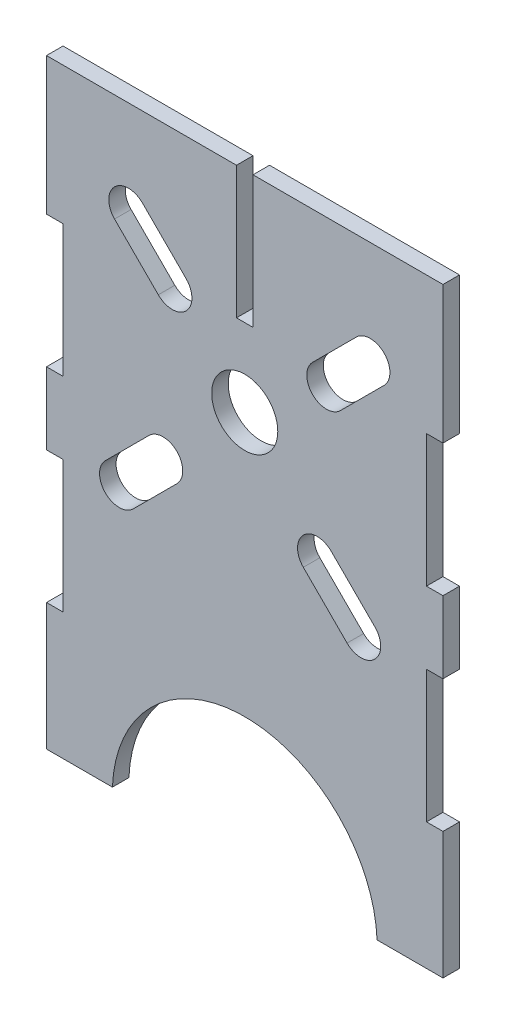
SolidWorks part; units mm, degrees
material "CARBON FIBERR"
ref_plane "Front Plane" through (0, 0, 0) normal (0, 0, 1) x (1, 0, 0)
ref_plane "Top Plane" through (0, 0, 0) normal (0, 1, 0) x (1, 0, 0)
ref_plane "Right Plane" through (0, 0, 0) normal (1, 0, 0) x (0, 0, -1)
sketch "Sketch9" plane through (0, 0, -50.8) normal (0, 0, 1) x (1, 0, 0)
  line L0 (24.1179, 20.5699) -> (15.7086, 12.1607) construction
  line L1 (1.5875, 14.9347) -> (-1.5875, 14.9347) construction
  line L2 (1.5875, 14.9347) -> (-1.5875, 14.9347)
  line L3 (-1.5875, 40.3347) -> (-1.5875, 14.9347) construction
  line L4 (-1.5875, 40.3347) -> (-1.5875, 14.9347)
  line L5 (1.5875, 40.3347) -> (1.5875, 14.9347) construction
  line L6 (1.5875, 40.3347) -> (1.5875, 14.9347)
  line L7 (-1.5875, 40.3347) -> (-38.1, 40.3347)
  line L8 (-38.1, 40.3347) -> (-38.1, -76.0967)
  line L9 (-38.1, -76.0967) -> (-25.4496, -76.0967)
  line L10 (25.4496, -76.0967) -> (38.1, -76.0967)
  line L11 (38.1, -76.0967) -> (38.1, 40.3347)
  line L12 (38.1, 40.3347) -> (1.5875, 40.3347)
  line L13 (1.5875, -76.0967) -> (-1.5875, -76.0967) construction
  line L14 (1.5875, -50.6967) -> (-1.5875, -50.6967) construction
  line L15 (1.5875, -50.6967) -> (-1.5875, -50.6967)
  line L16 (26.795, 17.8928) -> (18.3857, 9.4836)
  line L17 (21.4408, 23.247) -> (13.0315, 14.8378)
  line L18 (-22.3439, 22.3439) -> (-13.9347, 13.9347) construction
  line L19 (-22.3439, -22.3439) -> (22.3439, -22.3439) construction
  line L20 (-22.3439, -22.3439) -> (-22.3439, 22.3439) construction
  line L21 (-22.3439, 22.3439) -> (22.3439, 22.3439) construction
  line L22 (22.3439, -22.3439) -> (22.3439, 22.3439) construction
  line L23 (-22.3439, -22.3439) -> (22.3439, 22.3439) construction
  line L24 (-22.3439, 22.3439) -> (22.3439, -22.3439) construction
  line L25 (-19.6668, 25.021) -> (-11.2576, 16.6118)
  line L26 (-25.021, 19.6668) -> (-16.6118, 11.2576)
  line L27 (22.3439, -25.8918) -> (13.9347, -17.4826) construction
  line L28 (19.6668, -28.5689) -> (11.2576, -20.1597)
  line L29 (25.021, -23.2147) -> (16.6118, -14.8055)
  line L30 (-24.1179, -24.1179) -> (-15.7086, -15.7086) construction
  line L31 (-26.795, -21.4408) -> (-18.3857, -13.0315)
  line L32 (-21.4408, -26.795) -> (-13.0315, -18.3857)
  line L33 (-38.1, 39.3347) -> (-1.5875, 39.3347)
  line L34 (1.5875, 39.3347) -> (38.1, 39.3347)
  line L35 (38.1, 13.9347) -> (34.925, 13.9347)
  line L36 (34.925, 13.9347) -> (34.925, -11.4653)
  line L37 (34.925, -11.4653) -> (38.1, -11.4653)
  line L38 (38.1, -25.2967) -> (34.925, -25.2967)
  line L39 (34.925, -25.2967) -> (34.925, -50.6967)
  line L40 (34.925, -50.6967) -> (38.1, -50.6967)
  line L41 (-38.1, 13.9347) -> (-34.925, 13.9347)
  line L42 (-34.925, 13.9347) -> (-34.925, -11.4653)
  line L43 (-34.925, -11.4653) -> (-38.1, -11.4653)
  line L44 (-38.1, -25.2967) -> (-34.925, -25.2967)
  line L45 (-34.925, -25.2967) -> (-34.925, -50.6967)
  line L46 (-34.925, -50.6967) -> (-38.1, -50.6967)
  line L47 (-38.1, -75.0967) -> (-25.4299, -75.0967)
  line L48 (25.4299, -75.0967) -> (38.1, -75.0967)
  line L49 (-6.35, 0) -> (6.35, 0) construction
  arc A0 (-25.4496, -76.0967) -> (25.4496, -76.0967) centre (0, -76.0967) cw
  circle A1 centre (0, 0) radius 6.35
  arc A2 (-19.6668, 25.021) -> (-25.021, 19.6668) centre (-22.3439, 22.3439) ccw
  arc A3 (-16.6118, 11.2576) -> (-11.2576, 16.6118) centre (-13.9347, 13.9347) ccw
  arc A4 (26.795, 17.8928) -> (21.4408, 23.247) centre (24.1179, 20.5699) ccw
  arc A5 (13.0315, 14.8378) -> (18.3857, 9.4836) centre (15.7086, 12.1607) ccw
  arc A6 (19.6668, -28.5689) -> (25.021, -23.2147) centre (22.3439, -25.8918) ccw
  arc A7 (16.6118, -14.8055) -> (11.2576, -20.1597) centre (13.9347, -17.4826) ccw
  arc A8 (-26.795, -21.4408) -> (-21.4408, -26.795) centre (-24.1179, -24.1179) ccw
  arc A9 (-13.0315, -18.3857) -> (-18.3857, -13.0315) centre (-15.7086, -15.7086) ccw
  point P22 (-18.1393, 18.1393)
  point P32 (19.9132, 16.3653)
  point P39 (18.1393, -21.6872)
  point P46 (-19.9132, -19.9132)
  point P77 (0, 0)
  point P84 (0, 0)
  line M7 (-1.5875, 40.3347) -> (-1.5875, 14.9347)
  line M8 (-1.5875, 14.9347) -> (1.5875, 14.9347)
  line M9 (1.5875, 14.9347) -> (1.5875, 40.3347)
  dimension "D17" = 12.7
  dimension "D1" = 76.2
  dimension "D3" = 1
  dimension "D4" = 25.4
  dimension "D5" = 25.4
  dimension "D6" = 25.4
  dimension "D7" = 25.4
  dimension "D8" = 25.4
  dimension "D9" = 25.4
  dimension "D10" = 25.4
  dimension "D11" = 25.4
  dimension "D12" = 3.175
  dimension "D13" = 3.175
  dimension "D14" = 3.175
  dimension "D15" = 3.175
  dimension "D16" = 1
  dimension "D2" = 4
extrude "Boss-Extrude3" add sketch "Sketch9" against normal blind 3.175 contours L9 A0 L10 L11 L12 L7 L8 M9 M8 M7 | L8 L33 L7 M7 | L6 L34 L11 L12
